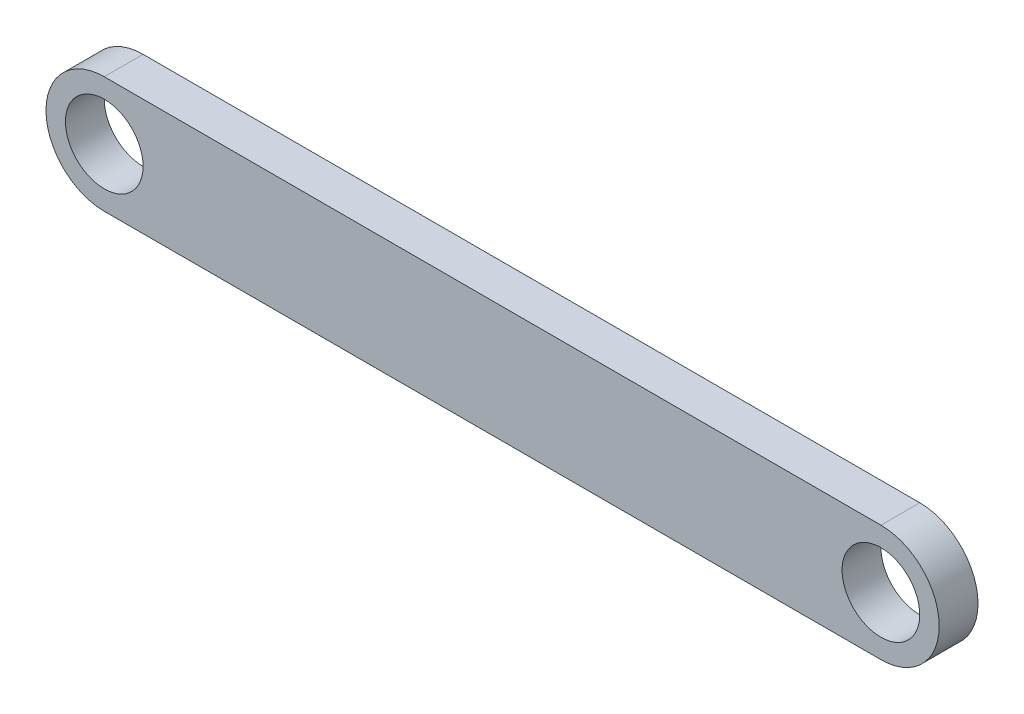
SolidWorks part; units mm, degrees
material "Alliage 6061"
ref_plane "Plan de face" through (0, 0, 0) normal (0, 0, 1) x (1, 0, 0)
ref_plane "Plan de dessus" through (0, 0, 0) normal (0, 1, 0) x (1, 0, 0)
ref_plane "Plan de droite" through (0, 0, 0) normal (1, 0, 0) x (0, 0, -1)
sketch "Esquisse1" plane through (0, 0, 0) normal (0, 0, 1) x (1, 0, 0)
  line L0 (0, 0) -> (-200, 0) construction
  line L1 (0, -15) -> (-200, -15)
  line L2 (0, 15) -> (-200, 15)
  arc A0 (0, -15) -> (0, 15) centre (0, 0) ccw
  arc A1 (-200, 15) -> (-200, -15) centre (-200, 0) ccw
  circle A2 centre (-200, 0) radius 10
  circle A3 centre (0, 0) radius 10
  point P3 (-100, 0)
  dimension "D3" = 20
  dimension "D1" = 30
  dimension "D2" = 200
extrude "Boss.-Extru.1" add sketch "Esquisse1" along normal mid plane 10
